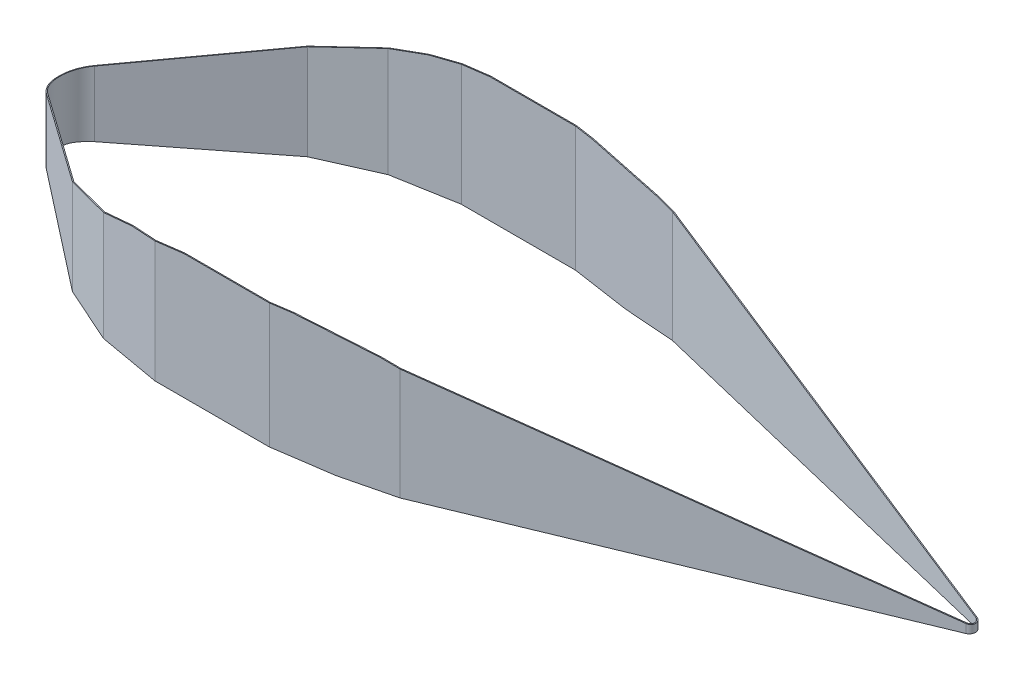
SolidWorks part; units mm, degrees
ref_plane "Front Plane" through (0, 0, 0) normal (0, 0, 1) x (1, 0, 0)
ref_plane "Top Plane" through (0, 0, 0) normal (0, 1, 0) x (1, 0, 0)
ref_plane "Right Plane" through (0, 0, 0) normal (1, 0, 0) x (0, 0, -1)
sketch "Sketch1" plane through (0, 0, 0) normal (0, 1, 0) x (1, 0, 0)
  line L0 (161.4098, 126.0887) -> (784.13, 612.54)
  line L1 (784.13, 612.54) -> (1076.464, 742.696)
  line L2 (1076.464, 742.696) -> (1401.451, 800)
  line L3 (1401.451, 800) -> (1997.019, 800)
  line L4 (1997.019, 800) -> (2590.582, 712.35)
  line L5 (2590.582, 712.35) -> (4854.8761, 28.7196)
  line L6 (4854.8761, -28.7196) -> (2590.582, -712.35)
  line L7 (2590.582, -712.35) -> (1997.019, -800)
  line L8 (1997.019, -800) -> (1401.451, -800)
  line L9 (1401.451, -800) -> (1076.464, -742.696)
  line L10 (1076.464, -742.696) -> (784.13, -612.54)
  line L11 (784.13, -612.54) -> (161.4098, -126.0887)
  arc A0 (161.4098, 126.0887) -> (161.4098, -126.0887) centre (259.9067, 0) ccw
  arc A1 (4854.8761, 28.7196) -> (4854.8761, -28.7196) centre (4846.2052, 0) cw
  point P15 (0, 0)
  point P18 (4950, 0)
  dimension "r0" = 160
  dimension "r6" = 30
  dimension "x1" = 784.13
  dimension "x2" = 1076.464
  dimension "x3" = 1401.451
  dimension "x4" = 1997.019
  dimension "x5" = 2590.582
  dimension "x6" = 4950
  dimension "x7" = 2590.582
  dimension "x8" = 1997.019
  dimension "x9" = 1401.451
  dimension "x10" = 1076.464
  dimension "x11" = 784.13
  dimension "y1" = 612.54
  dimension "y2" = 742.696
  dimension "y3" = 800
  dimension "y5" = 712.35
  dimension "y7" = 712.35
  dimension "y8" = 800
  dimension "y10" = 742.696
  dimension "y11" = 612.54
extrude "TopView_Extrude" add sketch "Sketch1" along normal blind 800
shell "Shell1" thickness 5
sketch "Sketch2" plane through (0, 0, 0) normal (0, 0, 1) x (1, 0, 0)
  line L0 (0, 300) -> (0, 332.8541)
  line L1 (113.6551, 478.3843) -> (1255.921, 763.655)
  line L2 (1255.921, 763.655) -> (1551.451, 800)
  line L3 (1551.451, 800) -> (2101.451, 800)
  line L4 (2101.451, 800) -> (2499.002, 768.799)
  line L5 (2499.002, 768.799) -> (4950, 381.685)
  line L6 (4950, 381.685) -> (4950, 359.158)
  line L7 (4950, 359.158) -> (2301.451, 150)
  line L8 (2301.451, 150) -> (150, 150)
  arc A0 (0, 300) -> (150, 150) centre (150, 300) ccw
  arc A1 (0, 332.8541) -> (113.6551, 478.3843) centre (150, 332.8541) cw
  point P12 (0, 150)
  point P15 (0, 450)
  dimension "r0" = 150
  dimension "r1" = 150
  dimension "x2" = 1255.921
  dimension "x3" = 1551.451
  dimension "x4" = 2101.451
  dimension "x5" = 2499.002
  dimension "x6" = 4950
  dimension "x8" = 2301.451
  dimension "y0" = 150
  dimension "y1" = 450
  dimension "y2" = 763.655
  dimension "y3" = 800
  dimension "y5" = 768.799
  dimension "y6" = 381.685
  dimension "y7" = 359.158
extrude "SideProfile_Cut" cut sketch "Sketch2" against normal through all and the other way through all flip side to cut
